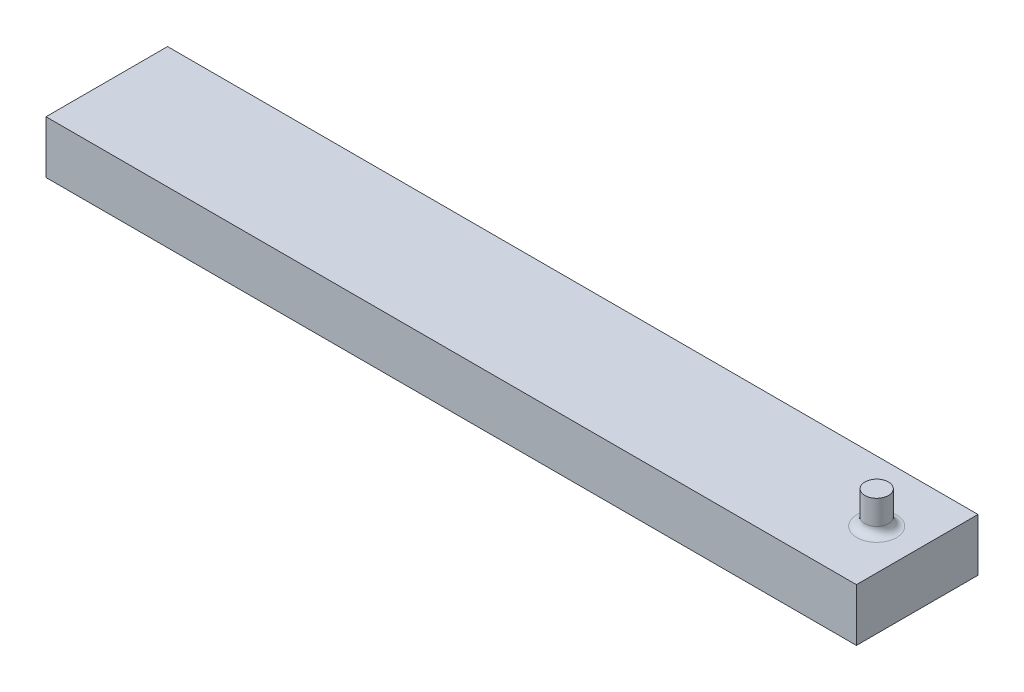
SolidWorks part; units mm, degrees
ref_plane "Front Plane" through (0, 0, 0) normal (0, 0, 1) x (1, 0, 0)
ref_plane "Top Plane" through (0, 0, 0) normal (0, 1, 0) x (1, 0, 0)
ref_plane "Right Plane" through (0, 0, 0) normal (1, 0, 0) x (0, 0, -1)
sketch "Sketch2" plane through (0, 0, 0) normal (0, 1, 0) x (1, 0, 0)
  line L1 (-50, -7.5) -> (50, -7.5)
  line L2 (-50, -7.5) -> (-50, 7.5)
  line L3 (-50, 7.5) -> (50, 7.5)
  line L4 (50, -7.5) -> (50, 7.5)
  line L5 (-50, -7.5) -> (50, 7.5) construction
  line L6 (-50, 7.5) -> (50, -7.5) construction
  point P0 (0, 0)
  dimension "D1" = 100
  dimension "D2" = 15
extrude "Boss-Extrude1" add sketch "Sketch2" along normal mid plane 6.5
sketch "Sketch4" plane through (0, 3.25, 0) normal (0, 1, 0) x (1, 0, 0)
  line L0 (50, -7.5) -> (50, 7.5) construction
  circle A0 centre (45, 0) radius 1.45
  dimension "D1" = 2.9
  dimension "D2" = 5
extrude "Boss-Extrude2" add sketch "Sketch4" along normal blind 4
sketch "Sketch5" plane through (0, -3.25, 0) normal (0, -1, 0) x (-1, 0, 0)
  line L1 (-3.575, 0) -> (3.575, 0) construction
  line L2 (50, 7.5) -> (50, -7.5) construction
  circle A0 centre (40, 0) radius 5.1
  dimension "D1" = 10.2
  dimension "D2" = 10
extrude "Cut-Extrude1" cut sketch "Sketch5" against normal blind 4
fillet "Fillet1" radius 1 1 edges at (45, 3.25, -1.45)
sketch "Sketch6" plane through (0, 0, 0) normal (0, 0, 1) x (1, 0, 0)
  line L0 (50, -3.25) -> (-50, -3.25) construction
  line L1 (-23.5, -3.25) -> (-15, -3.25)
  line L2 (-23.5, -3.25) -> (-23.5, 0.75)
  line L3 (-23.5, 0.75) -> (-15, 0.75)
  line L4 (-15, -3.25) -> (-15, 0.75)
  line L5 (-15, 0.75) -> (-10, 0.75)
  line L7 (-15, -2.5) -> (-10, -2.5)
  line L8 (-10, 0.75) -> (-10, -2.5)
  line L9 (-50, 3.25) -> (-50, -3.25) construction
  dimension "D1" = 8.5
  dimension "D2" = 5
  dimension "D3" = 3.25
  dimension "D4" = 0.75
  dimension "D5" = 35
  dimension "D6" = 4
extrude "Cut-Extrude3" cut sketch "Sketch6" against normal mid plane 2.25 contours L1 L4 L3 L2 | L8 L5 L4 L7
